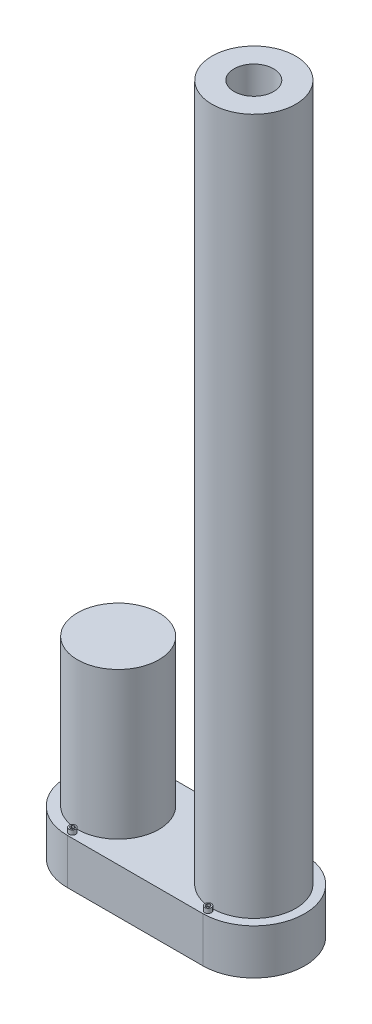
SolidWorks part; units mm, degrees
ref_plane "Front Plane" through (0, 0, 0) normal (0, 0, 1) x (1, 0, 0)
ref_plane "Top Plane" through (0, 0, 0) normal (0, 1, 0) x (1, 0, 0)
ref_plane "Right Plane" through (0, 0, 0) normal (1, 0, 0) x (0, 0, -1)
sketch "Sketch1" plane through (0, 0, 0) normal (0, 1, 0) x (1, 0, 0)
  line L0 (-30, 0) -> (30, 0) construction
  line L1 (-30, 22.5) -> (30, 22.5)
  line L2 (-30, -22.5) -> (30, -22.5)
  circle A0 centre (-30, 0) radius 22.5
  circle A1 centre (30, 0) radius 22.5
  dimension "D1" = 45
  dimension "D2" = 60
extrude "Boss-Extrude1" add sketch "Sketch1" along normal blind 20
sketch "Sketch2" plane through (0, 20, 0) normal (0, 1, 0) x (1, 0, 0)
  circle A0 centre (-30, 0) radius 18
  arc A1 (-30, 22.5) -> (-30, -22.5) centre (-30, 0) ccw construction
  dimension "D1" = 36
extrude "Boss-Extrude2" add sketch "Sketch2" along normal blind 65
sketch "Sketch3" plane through (0, 20, 0) normal (0, 1, 0) x (1, 0, 0)
  circle A0 centre (30, 0) radius 18.5
  arc A1 (30, -22.5) -> (30, 22.5) centre (30, 0) ccw construction
  dimension "D1" = 37
extrude "Boss-Extrude3" add sketch "Sketch3" along normal blind 308
sketch "Sketch4" plane through (0, 328, 0) normal (0, 1, 0) x (1, 0, 0)
  circle A0 centre (30, 0) radius 8.75
  circle A1 centre (30, 0) radius 18.5 construction
  dimension "D1" = 17.5
extrude "Cut-Extrude1" cut sketch "Sketch4" against normal blind 203.2
sketch "Sketch5" plane through (0, 124.8, 0) normal (0, 1, 0) x (1, 0, 0)
  circle A0 centre (30.4111, 0.1197) radius 3.6961
sketch "Sketch6" plane through (0, 0, 0) normal (0, -1, 0) x (1, 0, 0)
  circle A0 centre (30, 0) radius 18.5
  circle A1 centre (30, 0) radius 18.5 construction
sketch "Sketch7" plane through (0, 0, 0) normal (0, -1, 0) x (1, 0, 0)
  line L0 (-30, 0) -> (30, 0) construction
  line L1 (-30, 22.5) -> (30, 22.5)
  line L2 (-30, -22.5) -> (30, -22.5)
  arc A0 (-30, 22.5) -> (-30, -22.5) centre (-30, 0) ccw
  arc A1 (30, -22.5) -> (30, 22.5) centre (30, 0) ccw
  arc A2 (-30, 22.5) -> (-30, -22.5) centre (-30, 0) ccw construction
  arc A3 (30, -22.5) -> (30, 22.5) centre (30, 0) ccw construction
  point P2 (0, 0)
sketch "Sketch8" plane through (0, 20, 0) normal (0, 1, 0) x (1, 0, 0)
  line L0 (-30, -18) -> (-30, -22.5) construction
  circle A0 centre (-30, -20.25) radius 1
  circle A2 centre (-30, 0) radius 18 construction
  dimension "D1" = 2
extrude "Cut-Extrude2" cut sketch "Sketch8" against normal up to surface (20 mm away) up to face at (0, 0, 0)
sketch "Sketch9" plane through (0, 20, 0) normal (0, 1, 0) x (1, 0, 0)
  circle A0 centre (-30, -20.25) radius 1.5
  circle A1 centre (-30, -20.25) radius 1 construction
  dimension "D1" = 3
extrude "Boss-Extrude4" add sketch "Sketch9" along normal blind 2
sketch "Sketch10" plane through (0, 22, 0) normal (0, 1, 0) x (1, 0, 0)
  line L1 (-29.134, -20.75) -> (-29.134, -19.75)
  line L2 (-29.134, -19.75) -> (-30, -19.25)
  line L3 (-30, -19.25) -> (-30.866, -19.75)
  line L4 (-30.866, -19.75) -> (-30.866, -20.75)
  line L5 (-30.866, -20.75) -> (-30, -21.25)
  line L6 (-30, -21.25) -> (-29.134, -20.75)
  circle A0 centre (-30, -20.25) radius 0.866 construction
  circle A2 centre (-30, -20.25) radius 1.5 construction
  dimension "D1" = 1
extrude "Cut-Extrude3" cut sketch "Sketch10" against normal blind 1
sketch "Sketch11" plane through (0, 20, 0) normal (0, -1, 0) x (1, 0, 0)
  circle A0 centre (-30, 20.25) radius 1
  circle A1 centre (-30, 20.25) radius 1 construction
extrude "Boss-Extrude5" add sketch "Sketch11" along normal up to surface (20 mm away) up to face at (-30, 0, 21.25)
mirror "Mirror1" about plane through (0, 0, 0) normal (1, 0, 0) of "Boss-Extrude5", "Cut-Extrude3", "Boss-Extrude4", "Cut-Extrude2"
mirror "Mirror2" about plane through (0, 0, 0) normal (0, 0, 1) of "Mirror1", "Boss-Extrude4", "Cut-Extrude3"
